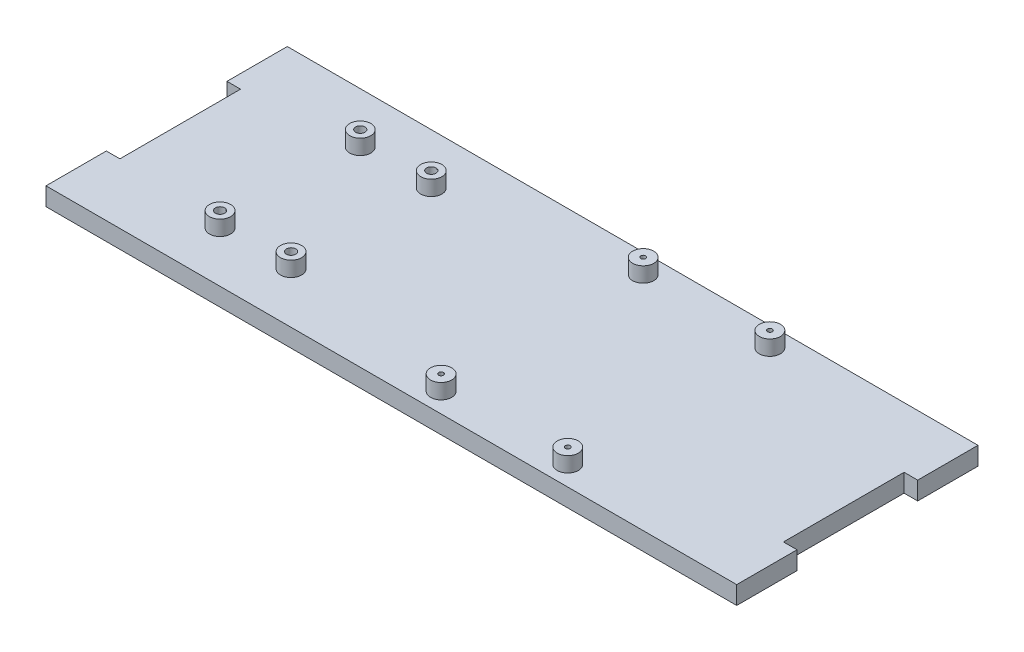
SolidWorks part; units mm, degrees
ref_plane "Front Plane" through (0, 0, 0) normal (0, 0, 1) x (1, 0, 0)
ref_plane "Top Plane" through (0, 0, 0) normal (0, 1, 0) x (1, 0, 0)
ref_plane "Right Plane" through (0, 0, 0) normal (1, 0, 0) x (0, 0, -1)
sketch "Sketch2" plane through (0, 0, 0) normal (0, 1, 0) x (1, 0, 0)
  line L1 (-110, 40) -> (110, 40)
  line L2 (-110, 40) -> (-110, -40)
  line L3 (-110, -40) -> (110, -40)
  line L4 (110, 40) -> (110, -40)
  line L5 (-110, 40) -> (110, -40) construction
  line L6 (-110, -40) -> (110, 40) construction
  point P0 (0, 0)
  dimension "D1" = 220
  dimension "D2" = 80
extrude "Main" add sketch "Sketch2" along normal blind 6
sketch "Sketch3" plane through (110, 0, 0) normal (1, 0, 0) x (0, 0, -1)
  line L0 (-40, 0) -> (40, 0) construction
  line L1 (40, 6) -> (20, 6)
  line L2 (40, 6) -> (40, 0)
  line L3 (40, 0) -> (20, 0)
  line L4 (20, 6) -> (20, 0)
  dimension "D1" = 20
extrude "Tab" add sketch "Sketch3" along normal blind 4.5
mirror "Mirror1" about plane through (0, 0, 0) normal (1, 0, 0) of "Tab" second plane through (0, 0, 0) second plane normal (0, 0, 1)
sketch "Sketch4" plane through (0, 6, 0) normal (0, 1, 0) x (1, 0, 0)
  line L0 (10, 33.5) -> (52, 33.5) construction
  line L1 (10, 33.5) -> (10, -33.5) construction
  line L2 (10, -33.5) -> (52, -33.5) construction
  line L3 (52, 33.5) -> (52, -33.5) construction
  line L4 (10, 33.5) -> (52, -33.5) construction
  line L5 (10, -33.5) -> (52, 33.5) construction
  line L6 (-73.55, 23.25) -> (-50, 23.25) construction
  line L7 (-73.55, 23.25) -> (-73.55, -23.25) construction
  line L8 (-73.55, -23.25) -> (-50, -23.25) construction
  line L9 (-50, 23.25) -> (-50, -23.25) construction
  line L10 (-73.55, 23.25) -> (-50, -23.25) construction
  line L11 (-73.55, -23.25) -> (-50, 23.25) construction
  circle A0 centre (10, 33.5) radius 0.8
  circle A1 centre (52, 33.5) radius 0.8
  circle A2 centre (52, -33.5) radius 0.8
  circle A3 centre (10, -33.5) radius 0.8
  circle A4 centre (-73.55, 23.25) radius 1.55
  circle A5 centre (-50, 23.25) radius 1.55
  circle A6 centre (-50, -23.25) radius 1.55
  circle A7 centre (-73.55, -23.25) radius 1.55
  point P0 (31, 0)
  point P9 (-61.775, 0)
  dimension "D3" = 1.6
  dimension "D6" = 3.1
  dimension "D1" = 42
  dimension "D2" = 67
  dimension "D4" = 23.55
  dimension "D5" = 46.5
  dimension "D7" = 50
  dimension "D8" = 10
extrude "PCB holes" cut sketch "Sketch4" against normal through all
sketch "Sketch5" plane through (0, 6, 0) normal (0, 1, 0) x (1, 0, 0)
  circle A0 centre (-73.55, 23.25) radius 3.5
  circle A1 centre (-50, 23.25) radius 3.5
  circle A2 centre (-73.55, -23.25) radius 3.5
  circle A3 centre (-50, -23.25) radius 3.5
  circle A4 centre (10, -33.5) radius 3.5
  circle A5 centre (52, -33.5) radius 3.5
  circle A6 centre (52, 33.5) radius 3.5
  circle A7 centre (10, 33.5) radius 3.5
  circle A8 centre (10, 33.5) radius 0.8 construction
  circle A9 centre (52, 33.5) radius 0.8 construction
  circle A10 centre (52, -33.5) radius 0.8 construction
  circle A11 centre (10, -33.5) radius 0.8 construction
  circle A12 centre (-50, -23.25) radius 1.55 construction
  circle A13 centre (-73.55, -23.25) radius 1.55 construction
  circle A14 centre (-50, 23.25) radius 1.55 construction
  circle A15 centre (-73.55, 23.25) radius 1.55 construction
  circle A16 centre (10, 33.5) radius 0.8
  circle A17 centre (52, 33.5) radius 0.8
  circle A18 centre (52, -33.5) radius 0.8
  circle A19 centre (10, -33.5) radius 0.8
  circle A20 centre (-50, -23.25) radius 1.55
  circle A21 centre (-73.55, -23.25) radius 1.55
  circle A22 centre (-50, 23.25) radius 1.55
  circle A23 centre (-73.55, 23.25) radius 1.55
  dimension "D1" = 7
extrude "PCB pegs" add sketch "Sketch5" along normal blind 5
equation "\"length\" = 215mm"
equation "\"width\" = 220mm"
equation "\"height\" = 100mm"
equation "\"skin_th\" = 6mm"
equation "\"shelf_height\" = 10mm"
equation "\"D1@Sketch2\"=\"width\""
equation "\"D1@Main\"=\"skin_th\""
equation "\"D1@Tab\"=\"skin_th\" * 1.5"
